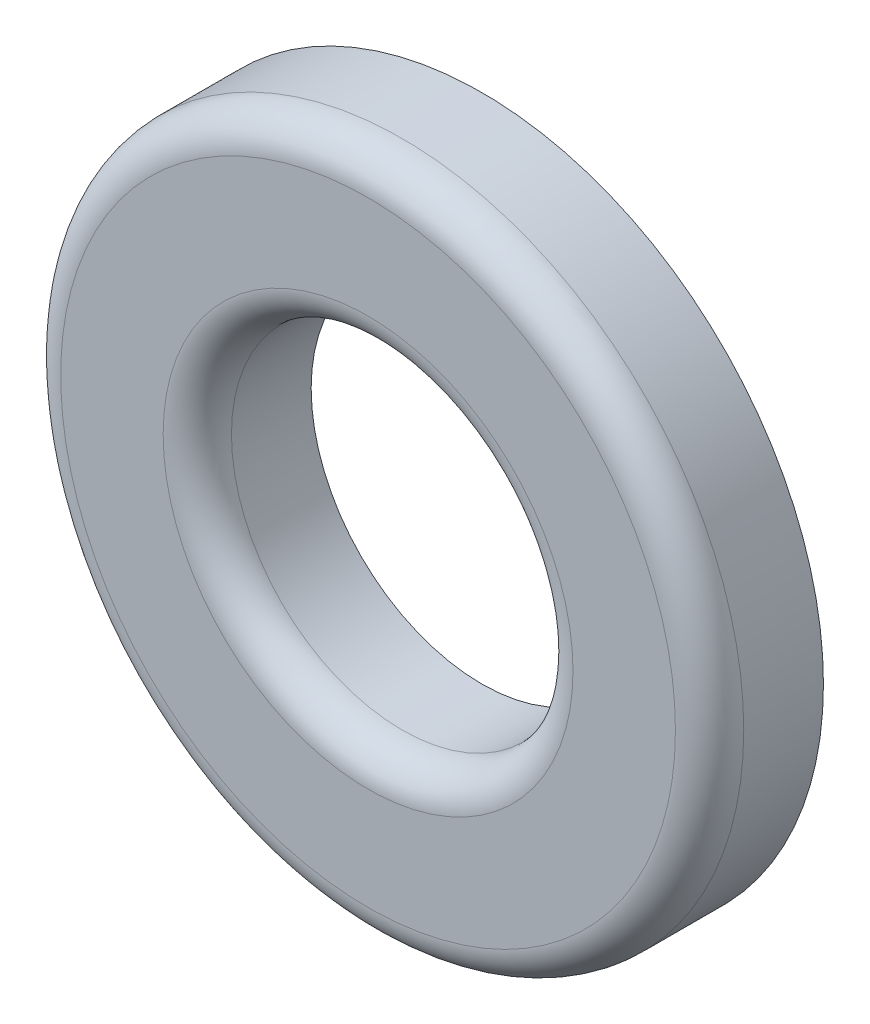
SolidWorks part; units mm, degrees
material "1.0037 (S235JR)"
ref_plane "Front Plane" through (0, 0, 0) normal (0, 0, 1) x (1, 0, 0)
ref_plane "Top Plane" through (0, 0, 0) normal (0, 1, 0) x (1, 0, 0)
ref_plane "Right Plane" through (0, 0, 0) normal (1, 0, 0) x (0, 0, -1)
sketch "Sketch1" plane through (0, 0, 0) normal (0, 0, 1) x (1, 0, 0)
  circle A0 centre (0, 0) radius 30
  circle A1 centre (0, 0) radius 15
  dimension "D1" = 60
  dimension "D2" = 30
extrude "Boss-Extrude1" add sketch "Sketch1" along normal blind 10
fillet "Fillet1" radius 3 2 edges at (15, 0, 10) (30, 0, 10)
